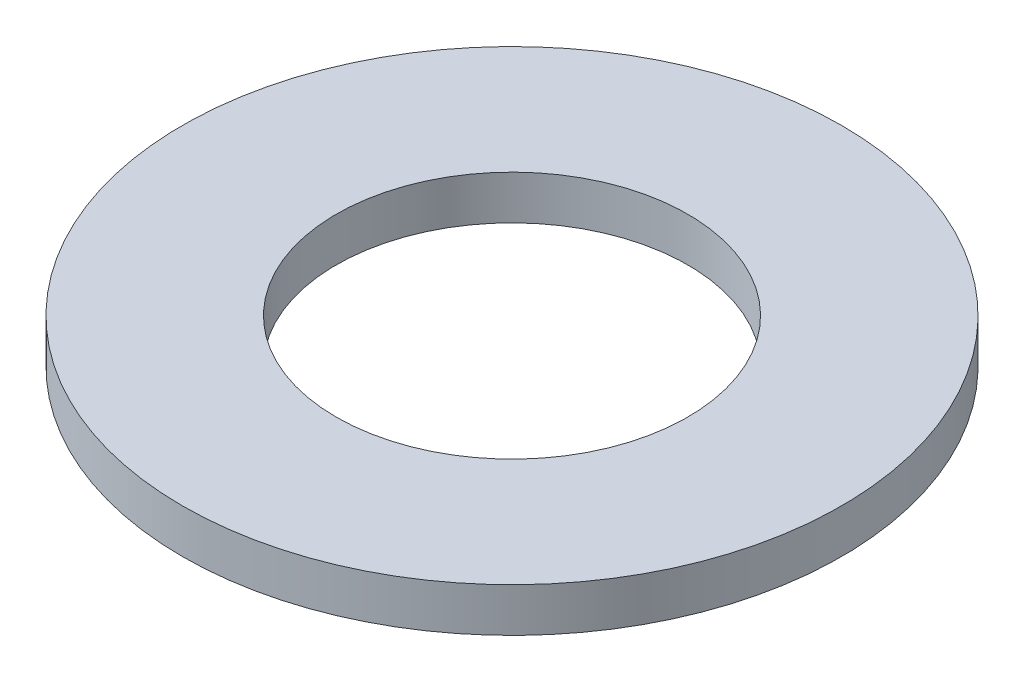
SolidWorks part; units mm, degrees
material "AISI 321 Annealed Stainless Steel (SS)"
ref_plane "Front Plane" through (0, 0, 0) normal (0, 0, 1) x (1, 0, 0)
ref_plane "Top Plane" through (0, 0, 0) normal (0, 1, 0) x (1, 0, 0)
ref_plane "Right Plane" through (0, 0, 0) normal (1, 0, 0) x (0, 0, -1)
sketch "Sketch1" plane through (0, 0, 0) normal (0, 1, 0) x (1, 0, 0)
  circle A0 centre (0, 0) radius 1.6
  circle A1 centre (0, 0) radius 3
  dimension "D1" = 3.2
  dimension "D2" = 6
extrude "Boss-Extrude1" add sketch "Sketch1" along normal blind 0.4
